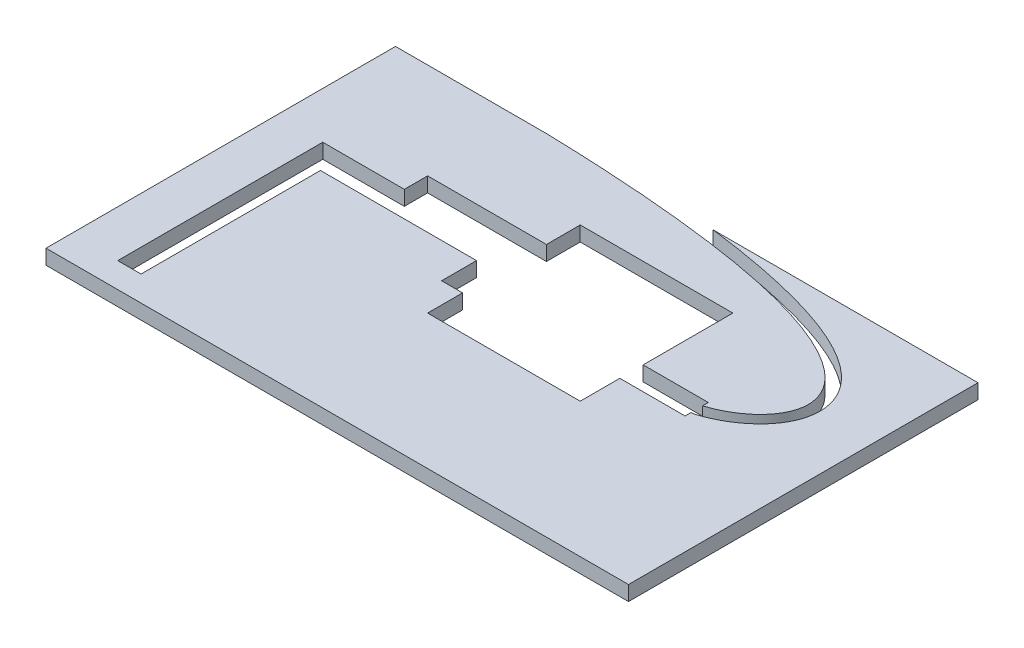
SolidWorks part; units mm, degrees
ref_plane "Front Plane" through (0, 0, 0) normal (0, 0, 1) x (1, 0, 0)
ref_plane "Top Plane" through (0, 0, 0) normal (0, 1, 0) x (1, 0, 0)
ref_plane "Right Plane" through (0, 0, 0) normal (1, 0, 0) x (0, 0, -1)
sketch "Sketch1" plane through (0, 0, 0) normal (0, 1, 0) x (1, 0, 0)
  line L0 (-105, -64.2155) -> (-95, -64.2155)
  line L1 (-125, -75) -> (125, -75)
  line L2 (-125, -75) -> (-125, 75)
  line L3 (-125, 75) -> (-60, 75)
  line L4 (125, -75) -> (125, 75)
  line L5 (-125, -75) -> (125, 75) construction
  line L6 (-125, 75) -> (125, -75) construction
  line L7 (-95, -64.2155) -> (-95, 12.7845)
  line L8 (-95, 12.7845) -> (-28, 12.7845)
  line L9 (-28, 12.7845) -> (-28, -2.2155)
  line L10 (-28, -2.2155) -> (-19, -2.2155)
  line L11 (-19, -2.2155) -> (-19, -17.2155)
  line L12 (-19, -17.2155) -> (46.5, -17.2155)
  line L13 (46.5, -17.2155) -> (46.5, -0.2155)
  line L14 (46.5, -0.2155) -> (74.5, -0.2155)
  line L15 (74.5, 2.2845) -> (75.9958, 2.5135)
  line L17 (11.3405, 75) -> (125, 75)
  line L18 (74.5, -0.2155) -> (74.5, 2.2845)
  line L19 (46.5, 9.7845) -> (46.5, 48.2845)
  line L20 (46.5, 48.2845) -> (-19, 48.2845)
  line L21 (-19, 48.2845) -> (-19, 33.7845)
  line L22 (-19, 33.7845) -> (-70, 33.7845)
  line L23 (-70, 33.7845) -> (-70, 23.7845)
  line L24 (-70, 23.7845) -> (-105, 23.7845)
  line L25 (-105, 23.7845) -> (-105, -64.2155)
  line L26 (13.75, 48.2845) -> (13.75, -17.2155) construction
  line L27 (74.5, 7.2845) -> (74.5, 9.7845)
  line L28 (74.5, 9.7845) -> (46.5, 9.7845)
  spline S0 degree 3 poles (74.5, 7.2845) (106.2499, 17.2387) (132.4367, 69.9032) (-60, 75) knots 0 0 0 0 1 1 1 1
  spline S1 degree 1 poles (75.9958, 2.5135) (-59.8676, 79.9982) knots 0 0 1 1 construction
  spline S2 degree 3 poles (75.9958, 2.5135) (80.4789, 3.919) (86.9559, 7.1041) (94.1279, 13.1583) (98.4533, 18.5916) (101.3135, 24.9426) (102.0697, 32.1109) (100.1253, 39.4914) (95.4705, 46.406) (88.2141, 52.7332) (78.1767, 58.5488) (65.0429, 63.8669) (48.4669, 68.6363) (31.4988, 72.0788) (15.8638, 74.4585) (3.066, 76.0413) (-10.8444, 77.407) (-23.397, 78.3512) (-34.0365, 78.9823) (-42.3177, 79.3916) (-49.4816, 79.6777) (-55.3563, 79.8722) (-58.3701, 79.9586) (-59.8676, 79.9982) knots 0 0 0 0 0.125 0.1875 0.25 0.3125 0.375 0.4375 0.5 0.5625 0.625 0.6875 0.75 0.8125 0.84375 0.875 0.90625 0.9375 0.953125 0.96875 0.984375 0.992188 1 1 1 1 only from (75.9958, 2.5135) to (11.3405, 75)
  point P0 (0, 0)
  dimension "D1" = 250
  dimension "D2" = 150
  dimension "D3" = 10
  dimension "D4" = 11
  dimension "D5" = 10
  dimension "D6" = 51
  dimension "D7" = 65.5
  dimension "D8" = 9
  dimension "D9" = 15
  dimension "D10" = 15
  dimension "D11" = 2.5
  dimension "D12" = 17
  dimension "D13" = 28
  dimension "D14" = 88
  dimension "D15" = 35
  dimension "D16" = 19
  dimension "D17" = 10
  dimension "D18" = 5
  dimension "D19" = 45
  dimension "D20" = 1.5132
  dimension "D23" = 17.2155
extrude "Boss-Extrude1" add sketch "Sketch1" along normal blind 6.35
